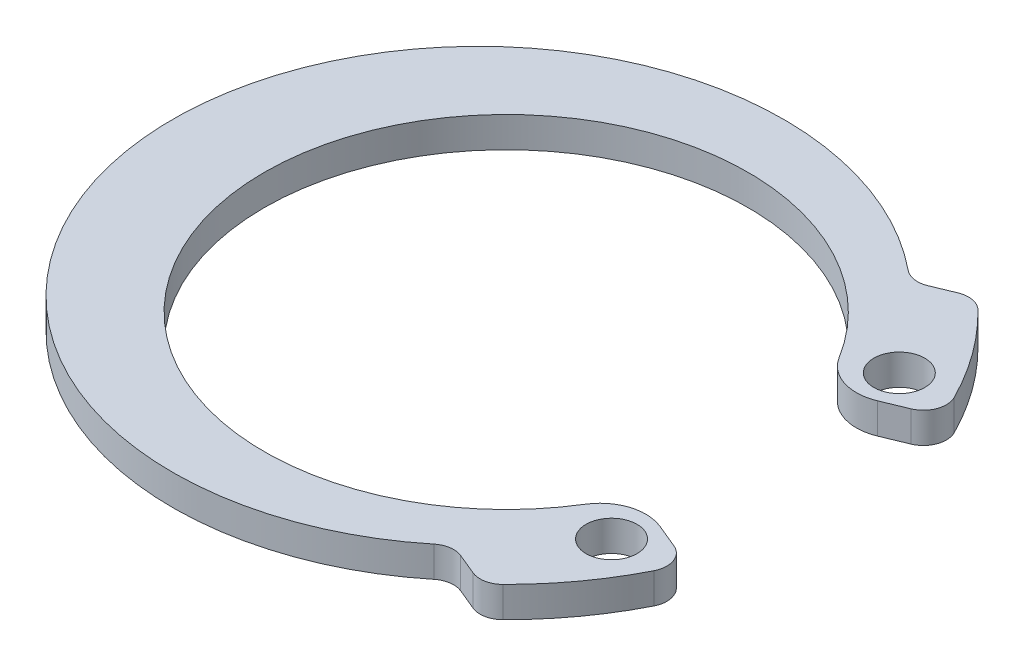
SolidWorks part; units mm, degrees
ref_plane "Front Plane" through (0, 0, 0) normal (0, 0, 1) x (1, 0, 0)
ref_plane "Top Plane" through (0, 0, 0) normal (0, 1, 0) x (1, 0, 0)
ref_plane "Right Plane" through (0, 0, 0) normal (1, 0, 0) x (0, 0, -1)
sketch "Sketch1" plane through (0, 0, 0) normal (0, 1, 0) x (1, 0, 0)
  line L0 (0, 0) -> (2.8916, 3.7684) construction
  line L1 (2.8916, 3.7684) -> (3.9874, 5.1965) construction
  line L2 (0, 0) -> (4.3884, 1.8177) construction
  line L3 (4.3884, 1.8177) -> (6.0514, 2.5066) construction
  line L4 (0, 0) -> (4.3884, -1.8177) construction
  line L5 (4.3884, -1.8177) -> (6.0514, -2.5066) construction
  line L6 (0, 0) -> (2.8916, -3.7684) construction
  line L7 (2.8916, -3.7684) -> (3.9874, -5.1965) construction
  line L8 (5.0194, -3.8515) -> (0, 0) construction
  line L9 (0, 0) -> (6.55, 0) construction
  line L10 (6.0514, 2.5066) -> (6.0514, -2.5066) construction
  line L11 (6.0514, -2.5066) -> (3.9874, -5.1965) construction
  line L12 (6.0514, 2.5066) -> (3.9874, 5.1965) construction
  line L13 (5.0194, 3.8515) -> (0, 0) construction
  line L14 (-4.75, 0) -> (-6.55, 0) construction
  circle A0 centre (0, 0) radius 6.55 construction
  circle A1 centre (0, 0) radius 4.75 construction
  arc A4 (5.2199, 2.1622) -> (4.4824, 3.4395) centre (0, 0) ccw construction
  arc A7 (5.2199, -2.1622) -> (4.4824, -3.4395) centre (0, 0) cw construction
  circle A8 centre (4.893, -2.825) radius 0.5 construction
  circle A9 centre (4.893, 2.825) radius 0.5 construction
  point P20 (6.0514, 0)
  dimension "Ring OD" = 13.1
  dimension "R" = 1
  dimension "D1" = 30
  dimension "D3" = 45
  dimension "S" = 1.8
sketch "Sketch2" plane through (0, 0, 0) normal (1, 0, 0) x (0, 0, -1)
  line L3 (6.55, 0) -> (-6.55, 0) construction
  line L7 (6.55, 0.3) -> (6.55, -0.3) construction
  dimension "Ring Thickness" = 0.6
sketch "Sketch3" plane through (0, 0, 0) normal (0, 1, 0) x (1, 0, 0)
  line L1 (-6.55, 0) -> (-4.75, 0) construction
  line L2 (4.3884, -1.8177) -> (6.0514, -2.5066) construction
  line L3 (2.8916, -3.7684) -> (3.9874, -5.1965) construction
  line L5 (3.6937, 4.5877) -> (4.1099, 4.7601)
  line L6 (5.1533, 2.1346) -> (5.6203, 2.328)
  line L7 (5.1533, -2.1346) -> (5.6203, -2.328)
  line L8 (3.6937, -4.5877) -> (4.1099, -4.7601)
  line L9 (2.8916, 3.7684) -> (3.9874, 5.1965) construction
  line L10 (4.3884, 1.8177) -> (6.0514, 2.5066) construction
  line L11 (0, 0) -> (4.3884, 1.8177) construction
  arc A1 (4.0428, 2.4936) -> (4.0428, -2.4936) centre (0, 0) ccw
  circle A2 centre (0, 0) radius 4.75 construction
  arc A3 (3.2374, 4.6544) -> (3.2374, -4.6544) centre (-0.5496, 0) ccw
  circle A4 centre (0, 0) radius 6.55 construction
  arc A6 (4.598, 4.6649) -> (5.85, 2.9462) centre (0, 0) cw
  arc A7 (4.1099, -4.7601) -> (4.598, -4.6649) centre (4.2821, -4.3444) ccw
  arc A8 (4.598, -4.6649) -> (5.85, -2.9462) centre (0, 0) ccw
  circle A9 centre (4.893, -2.825) radius 0.5
  circle A10 centre (4.893, 2.825) radius 0.5
  circle A11 centre (4.893, 2.825) radius 0.5 construction
  circle A12 centre (4.893, -2.825) radius 0.5 construction
  arc A13 (3.2374, -4.6544) -> (3.6937, -4.5877) centre (3.5215, -5.0035) cw
  arc A14 (5.6203, -2.328) -> (5.85, -2.9462) centre (5.4481, -2.7438) cw
  arc A15 (5.1533, -2.1346) -> (4.0428, -2.4936) centre (4.8089, -2.966) ccw
  arc A16 (5.1533, 2.1346) -> (4.0428, 2.4936) centre (4.8089, 2.966) cw
  arc A17 (5.6203, 2.328) -> (5.85, 2.9462) centre (5.4481, 2.7438) ccw
  arc A18 (4.1099, 4.7601) -> (4.598, 4.6649) centre (4.2821, 4.3444) cw
  arc A19 (3.2374, 4.6544) -> (3.6937, 4.5877) centre (3.5215, 5.0035) ccw
  arc A20 (5.2199, 2.1622) -> (4.4824, 3.4395) centre (0, 0) ccw construction
  arc A21 (4.4824, -3.4395) -> (5.2199, -2.1622) centre (0, 0) ccw construction
  point P24 (3.4395, 4.4824)
  point P30 (3.4395, -4.4824)
  dimension "D1" = 0.45
  dimension "D2" = 0.9
extrude "Boss-Extrude1" add sketch "Sketch3" along normal up to vertex (0.3 mm away) and the other way up to vertex (0.3 mm away) up to point (0, 0.3, -6.55) other way up to point (0, -0.3, -6.55)
sketch "Sketch4" plane through (0, 0, 0) normal (0, 1, 0) x (1, 0, 0)
  line L0 (0, -5.9752) -> (0, 5.9752) construction
  arc A0 (3.2374, 4.6544) -> (3.2374, -4.6544) centre (-0.5496, 0) ccw construction
  point P7 (0, 0)
  point P9 (0, -5.9752)
sketch "Esquisse1" plane through (0, 0.3, 0) normal (0, 1, 0) x (1, 0, 0)
  circle A0 centre (0, 0) radius 6 construction
  circle A1 centre (0, 0) radius 4 construction
  dimension "D1" = 12
  dimension "D2" = 8
equation "\"D1@Sketch3\"=\"S@Sketch1\"/4"
equation "\"D2@Sketch3\"=\"S@Sketch1\"/2"
